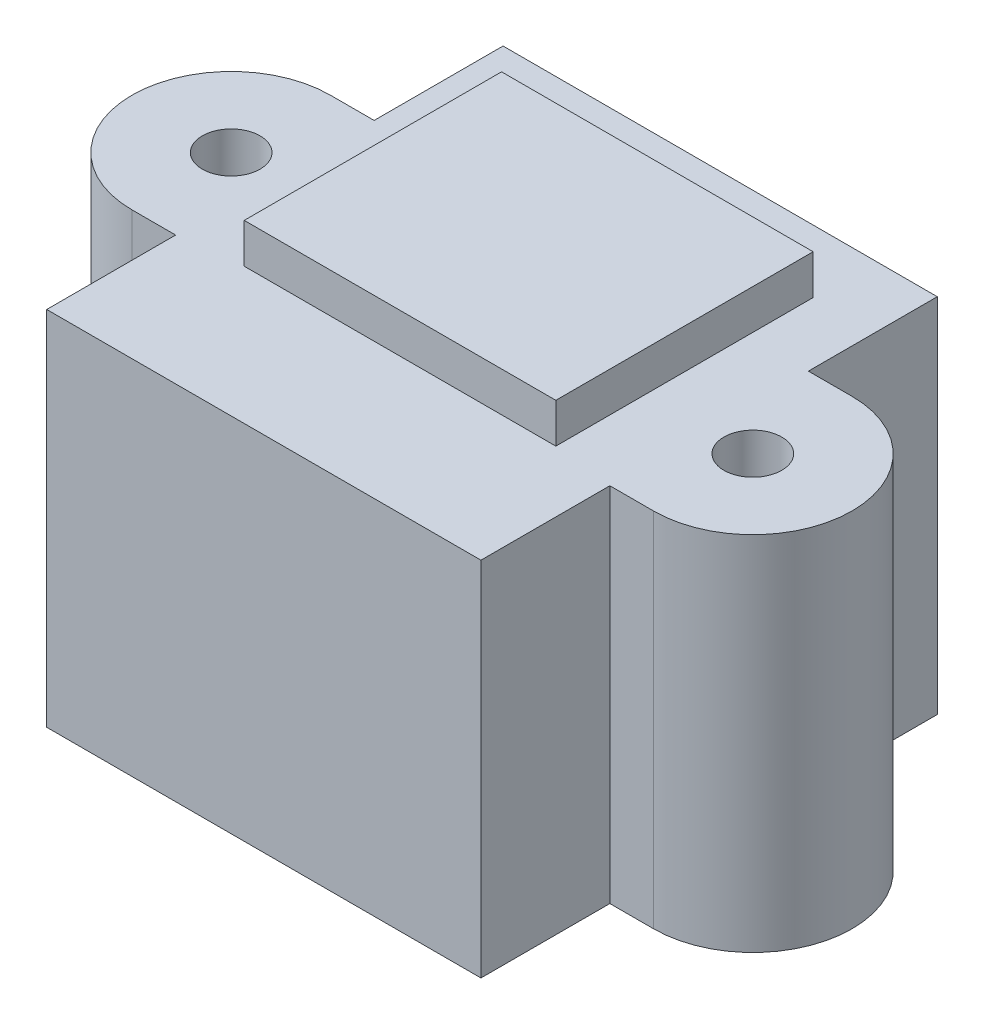
SolidWorks part; units mm, degrees
ref_plane "Front Plane" through (0, 0, 0) normal (0, 0, 1) x (1, 0, 0)
ref_plane "Top Plane" through (0, 0, 0) normal (0, 1, 0) x (1, 0, 0)
ref_plane "Right Plane" through (0, 0, 0) normal (1, 0, 0) x (0, 0, -1)
sketch "Sketch1" plane through (0, 0, 0) normal (0, 1, 0) x (1, 0, 0)
  line L0 (0, 11.5316) -> (0, -11.5316) construction
  line L1 (-10.9728, -11.5316) -> (10.9728, -11.5316)
  line L2 (-10.9728, -11.5316) -> (-10.9728, 11.5316)
  line L3 (-10.9728, 11.5316) -> (10.9728, 11.5316)
  line L4 (10.9728, -11.5316) -> (10.9728, 11.5316)
  line L5 (-10.9728, -11.5316) -> (10.9728, 11.5316) construction
  line L6 (-10.9728, 11.5316) -> (10.9728, -11.5316) construction
  line L7 (-13.1826, 5.0165) -> (13.1826, 5.0165)
  line L8 (-18.1991, 0) -> (18.1991, 0) construction
  line L9 (-13.1826, -5.0165) -> (13.1826, -5.0165)
  arc A0 (-13.1826, 5.0165) -> (-13.1826, -5.0165) centre (-13.1826, 0) ccw
  arc A1 (13.1826, 5.0165) -> (13.1826, -5.0165) centre (13.1826, 0) cw
  point P0 (0, 0)
  point P6 (0, 0)
  point P16 (0, 0)
  dimension "D1" = 23.0632
  dimension "D2" = 21.9456
  dimension "D3" = 10.033
  dimension "D4" = 26.3652
extrude "Boss-Extrude1" add sketch "Sketch1" along normal blind 18.288 contours L7 A0 L9 L2 | L2 L9 L4 L7 | L9 L2 L1 L4 | A1 L7 L4 L9 | L2 L7 L4 L3
sketch "Sketch2" plane through (0, 18.288, 0) normal (0, 1, 0) x (1, 0, 0)
  line L0 (0, 11.5316) -> (0, -11.5316) construction
  line L1 (-7.874, 8.3566) -> (7.874, 8.3566)
  line L2 (-7.874, 8.3566) -> (-7.874, -4.6482)
  line L3 (-7.874, -4.6482) -> (7.874, -4.6482)
  line L4 (7.874, 8.3566) -> (7.874, -4.6482)
  line L5 (-7.874, 8.3566) -> (7.874, -4.6482) construction
  line L6 (-7.874, -4.6482) -> (7.874, 8.3566) construction
  line L7 (-10.9728, 11.5316) -> (10.9728, 11.5316) construction
  line L8 (-10.9728, -11.5316) -> (10.9728, -11.5316) construction
  point P0 (0, 1.8542)
  point P11 (0, 2.8417)
  dimension "D1" = 13.0048
  dimension "D2" = 15.748
  dimension "D3" = 3.175
extrude "Boss-Extrude2" add sketch "Sketch2" along normal blind 2.0066
sketch "Sketch3" plane through (0, 18.288, 0) normal (0, 1, 0) x (1, 0, 0)
  circle A0 centre (-13.1826, 0) radius 1.4605
  circle A1 centre (13.1826, 0) radius 1.4605
  dimension "D1" = 2.921
extrude "Cut-Extrude1" cut sketch "Sketch3" against normal through all
ref_plane "Plane1" through (0, 0, -1.8542) normal (0, 0, -1) x (-1, 0, 0)
ref_plane "Plane2" through (0, 0, 0) normal (-1, 0, 0) x (0, 0, 1)
equation "\"D4@Sketch1\"=1.433in-\"D3@Sketch1\""
